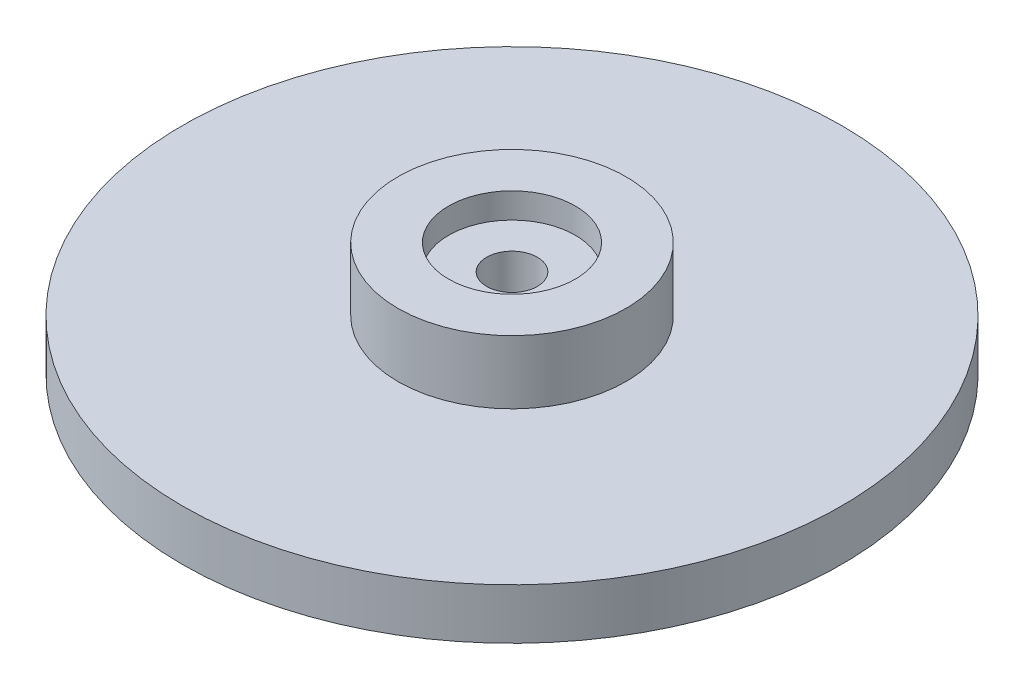
SolidWorks part; units mm, degrees
ref_plane "前视基准面" through (0, 0, 0) normal (0, 0, 1) x (1, 0, 0)
ref_plane "上视基准面" through (0, 0, 0) normal (0, 1, 0) x (1, 0, 0)
ref_plane "右视基准面" through (0, 0, 0) normal (1, 0, 0) x (0, 0, -1)
other "Configuration Table"
sketch "草图2" plane through (0, 0, 0) normal (0, 1, 0) x (1, 0, 0)
  circle A0 centre (0, 0) radius 13
extrude "凸台-拉伸1" add sketch "草图2" along normal blind 2
sketch "草图3" plane through (0, 2, 0) normal (0, 1, 0) x (1, 0, 0)
  circle A0 centre (0, 0) radius 4.5
  circle A2 centre (0, 0) radius 2.5
extrude "凸台-拉伸2" add sketch "草图3" along normal blind 2.5
sketch "草图4" plane through (0, 2, 0) normal (0, 1, 0) x (1, 0, 0)
  circle A2 centre (0, 0) radius 2.5
  circle A3 centre (0, 0) radius 2.5
  dimension "D1" = 0
extrude "凸台-拉伸3" add sketch "草图4" along normal blind 1.5
sketch "草图5" plane through (0, 0, 0) normal (0, -1, 0) x (1, 0, 0)
  circle A0 centre (0, 0) radius 2.6
extrude "切除-拉伸1" cut sketch "草图5" against normal blind 2
sketch "草图6" plane through (0, 2, 0) normal (0, -1, 0) x (1, 0, 0)
  circle A0 centre (0, 0) radius 1
extrude "切除-拉伸2" cut sketch "草图6" against normal blind 2
